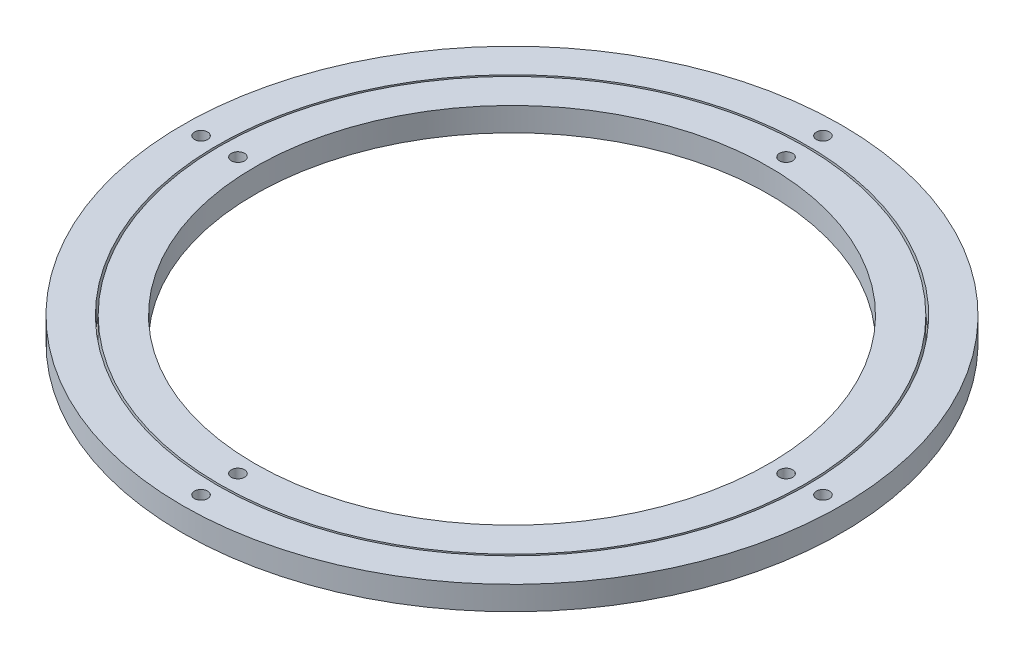
SolidWorks part; units mm, degrees
material "普通碳钢"
ref_plane "前视" through (0, 0, 0) normal (0, 0, 1) x (1, 0, 0)
ref_plane "上视" through (0, 0, 0) normal (0, 1, 0) x (1, 0, 0)
ref_plane "右视" through (0, 0, 0) normal (1, 0, 0) x (0, 0, -1)
sketch "Sketch1" plane through (0, 0, 0) normal (0, 1, 0) x (1, 0, 0)
  line L0 (0, 125) -> (0, -125) construction
  circle A0 centre (0, 0) radius 125
  circle A1 centre (0, 0) radius 111.75
  point P12 (0, 0)
  point P13 (0, 0)
  dimension "D1" = 250
  dimension "D2" = 223.5
extrude "Boss-Extrude1" add sketch "Sketch1" along normal blind 9
sketch "Sketch2" plane through (0, 0, 0) normal (0, 1, 0) x (1, 0, 0)
  line L0 (-125, 0) -> (125, 0) construction
  line L1 (0, 125) -> (0, -125) construction
  circle A0 centre (0, 0) radius 111
  circle A1 centre (0, 0) radius 97.5
  circle A2 centre (0, 0) radius 125 construction
  dimension "D1" = 222
  dimension "D2" = 195
extrude "Boss-Extrude2" add sketch "Sketch2" along normal blind 9 separate body
sketch "草图1" plane through (0, 9, 0) normal (0, 1, 0) x (1, 0, 0)
  line L0 (0, 103.9457) -> (0, -103.9457) construction
  line L1 (-103.9457, 0) -> (103.9457, 0) construction
  circle A2 centre (0, 103.9457) radius 2.5
  circle A3 centre (0, 0) radius 103.9457 construction
  circle A4 centre (103.9457, 0) radius 2.5
  circle A5 centre (0, -103.9457) radius 2.5
  circle A6 centre (-103.9457, 0) radius 2.5
  point P4 (0, 0)
  point P5 (0, 0)
  point P15 (0, 0)
  point P25 (0, 0)
  dimension "D1" = 5
  dimension "D2" = 103.9457
  dimension "D3" = 4
extrude "切除-拉伸1" cut sketch "草图1" against normal blind 10
sketch "草图2" plane through (0, 9, 0) normal (0, 1, 0) x (1, 0, 0)
  circle A0 centre (0, 117.9457) radius 2.5
  circle A1 centre (0, 0) radius 117.9457 construction
  circle A2 centre (117.9457, 0) radius 2.5
  circle A3 centre (0, -117.9457) radius 2.5
  circle A4 centre (-117.9457, 0) radius 2.5
  point P15 (0, 0)
  dimension "D1" = 5
  dimension "D2" = 14
  dimension "D3" = 4
extrude "切除-拉伸2" cut sketch "草图2" against normal blind 10
